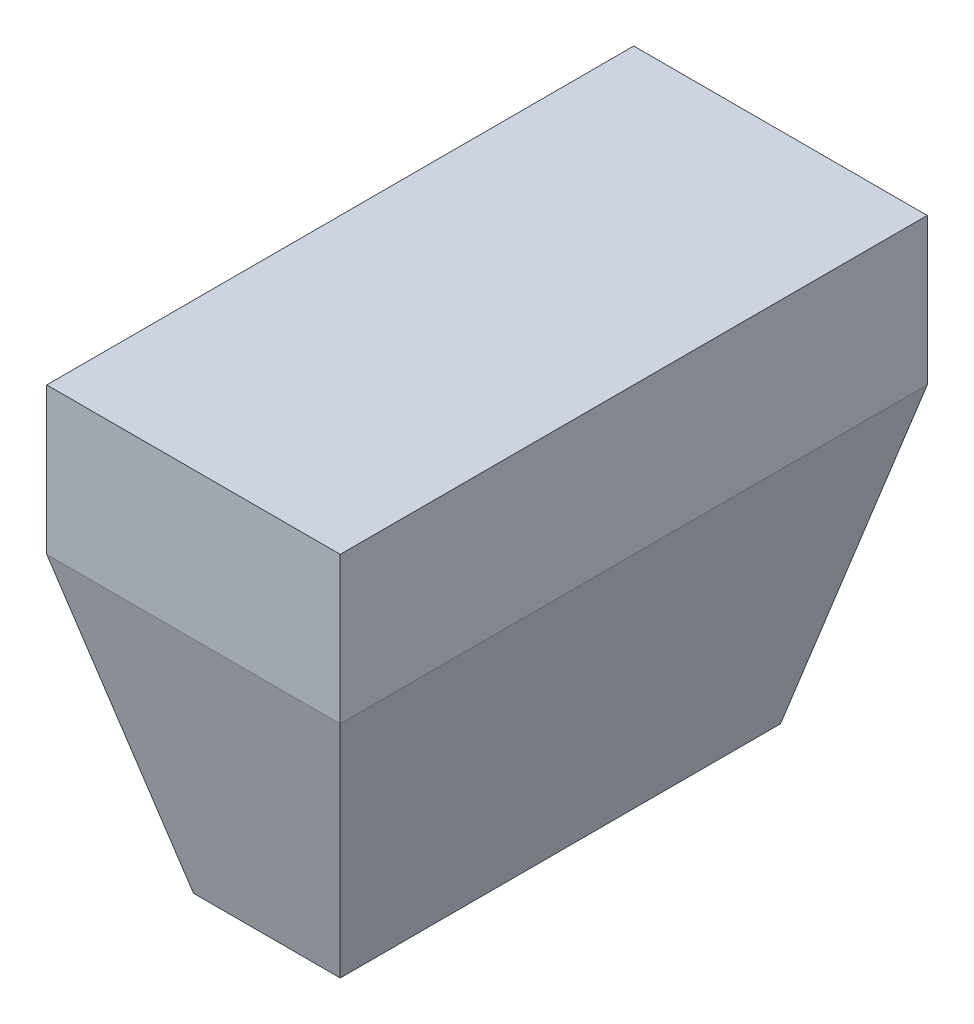
SolidWorks part; units mm, degrees
ref_plane "Front Plane" through (0, 0, 0) normal (0, 0, 1) x (1, 0, 0)
ref_plane "Top Plane" through (0, 0, 0) normal (0, 1, 0) x (1, 0, 0)
ref_plane "Right Plane" through (0, 0, 0) normal (1, 0, 0) x (0, 0, -1)
sketch "Sketch1" plane through (0, 0, 0) normal (0, 1, 0) x (1, 0, 0)
  line L1 (25.4, 50.8) -> (-25.4, 50.8)
  line L2 (25.4, 50.8) -> (25.4, -50.8)
  line L3 (25.4, -50.8) -> (-25.4, -50.8)
  line L4 (-25.4, 50.8) -> (-25.4, -50.8)
  line L5 (25.4, 50.8) -> (-25.4, -50.8) construction
  line L6 (25.4, -50.8) -> (-25.4, 50.8) construction
  point P0 (0, 0)
  dimension "D1" = 101.6
  dimension "D2" = 50.8
extrude "Boss-Extrude1" add sketch "Sketch1" along normal blind 76.2
chamfer "Chamfer1" distance 12.7 distance2 50.8 1 edges at (25.4, 0, 0)
chamfer "Chamfer2" distance 12.7 distance2 50.8 1 edges at (-25.4, 0, 0)
chamfer "Chamfer3" distance 12.7 distance2 50.8 1 edges at (0, 0, 50.8)
chamfer "Chamfer4" distance 12.7 distance2 50.8 1 edges at (0, 0, -50.8)
